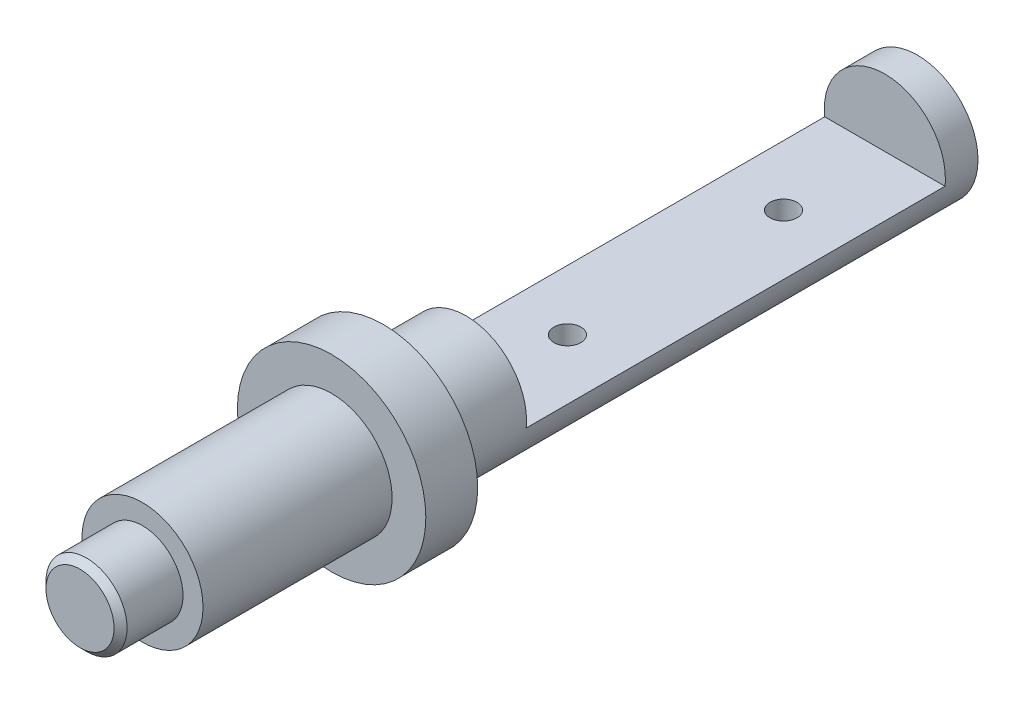
SolidWorks part; units mm, degrees
material "Chrome Stainless Steel"
ref_plane "Front Plane" through (0, 0, 0) normal (0, 0, 1) x (1, 0, 0)
ref_plane "Top Plane" through (0, 0, 0) normal (0, 1, 0) x (1, 0, 0)
ref_plane "Right Plane" through (0, 0, 0) normal (1, 0, 0) x (0, 0, -1)
sketch "Sketch1" plane through (0, 0, 0) normal (1, 0, 0) x (0, 0, -1)
  line L0 (-76.3671, 0) -> (76.3671, 0) construction
  line L1 (192.6, 0) -> (192.6, 28)
  line L2 (192.6, 28) -> (-54.5, 28)
  line L3 (-54.5, 28) -> (-54.5, 43.6)
  line L4 (-54.5, 43.6) -> (-78.5, 43.6)
  line L5 (-78.5, 43.6) -> (-78.5, 28)
  line L6 (-78.5, 28) -> (-166, 28)
  line L7 (-166, 28) -> (-166, 18.75)
  line L8 (-166, 18.75) -> (-194.9, 18.75)
  line L9 (-194.9, 18.75) -> (-194.9, 0)
  line L10 (192.6, 0) -> (-194.9, 0)
  point P3 (-194.9, 9.375)
  point P4 (0, 0)
  dimension "D1" = 43.6
  dimension "D2" = 28
  dimension "D3" = 18.75
  dimension "D4" = 28
  dimension "D5" = 24
  dimension "D6" = 247.1
  dimension "D7" = 87.5
  dimension "D8" = 28.9
  dimension "D9" = 194.9
revolve "Revolve1" add sketch "Sketch1" angle 360 about L0
sketch "Sketch2" plane through (0, 0, 0) normal (1, 0, 0) x (0, 0, -1)
  line L0 (-54.5, -43.6) -> (-54.5, 43.6) construction
  line L1 (-16.3, -3.1) -> (177.5, -3.1)
  line L2 (-16.3, -3.1) -> (-16.3, 34.8101)
  line L3 (-16.3, 34.8101) -> (177.5, 34.8101)
  line L4 (177.5, -3.1) -> (177.5, 34.8101)
  line L6 (192.6, 28) -> (-54.5, 28) construction
  dimension "D1" = 193.8
  dimension "D2" = 38.2
  dimension "D3" = 31.1
  dimension "D4" = 34.8101
extrude "Cut-Extrude1" cut sketch "Sketch2" against normal through all both and the other way through all contours L1 L4 L3 L2
sketch "Sketch3" plane through (0, 0, 0) normal (0, 1, 0) x (1, 0, 0)
  line L0 (0, 226.3081) -> (0, -226.3081) construction
  line L1 (28, -16.3) -> (-28, -16.3) construction
  line L2 (43.6, -54.5) -> (-43.6, -54.5) construction
  circle A0 centre (0, 30.6) radius 6.25
  circle A1 centre (0, 130.6) radius 6.25
  point P4 (0, 0)
  dimension "D1" = 12.5
  dimension "D2" = 12.5
  dimension "D3" = 46.9
  dimension "D4" = 100
  dimension "D5" = 38.2
extrude "Cut-Extrude2" cut sketch "Sketch3" against normal through all and the other way through all
chamfer "Chamfer1" distance 3 angle 45 1 edges at (18.75, 0, 194.9)
